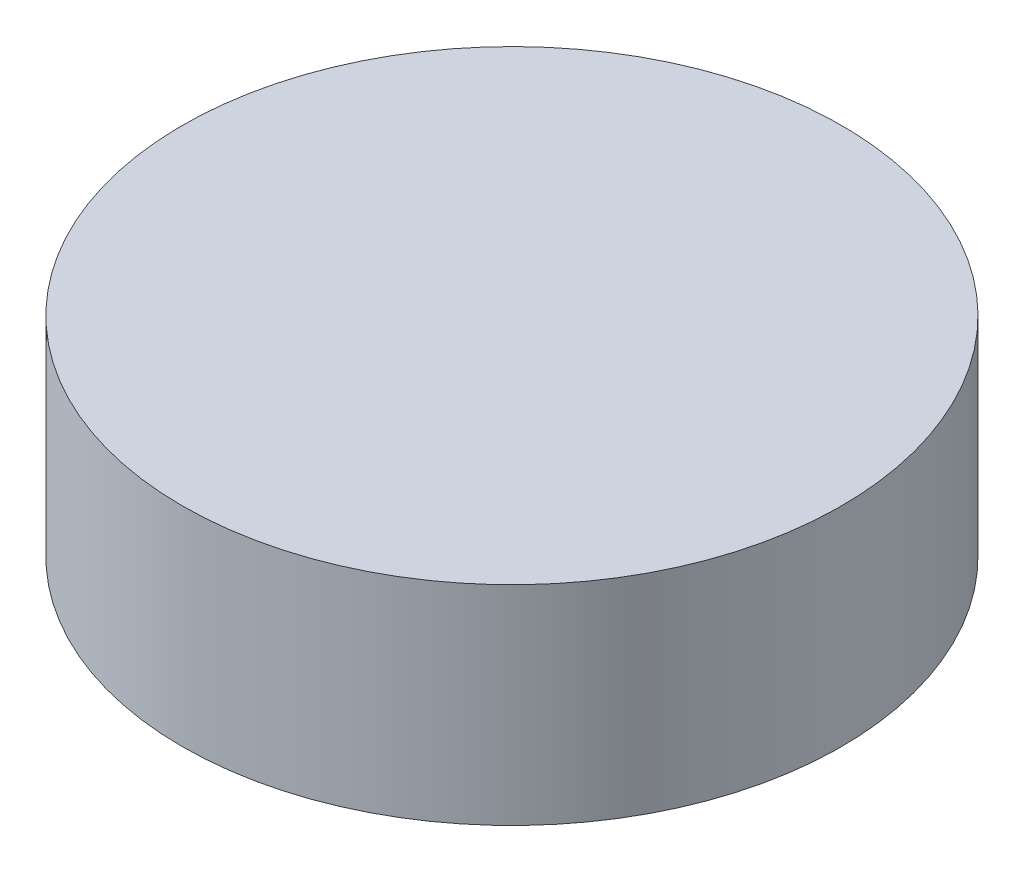
SolidWorks part; units mm, degrees
material "ABS"
ref_plane "Front Plane" through (0, 0, 0) normal (0, 0, 1) x (1, 0, 0)
ref_plane "Top Plane" through (0, 0, 0) normal (0, 1, 0) x (1, 0, 0)
ref_plane "Right Plane" through (0, 0, 0) normal (1, 0, 0) x (0, 0, -1)
ref_plane "Plane1" through (0, 93.4276, 0) normal (0, 1, 0) x (1, 0, 0)
sketch "Sketch2" plane through (0, 93.4276, 0) normal (0, 1, 0) x (1, 0, 0)
  circle A0 centre (47.2924, -96.3529) radius 63.5 construction
  circle A2 centre (47.2924, -96.3529) radius 70.25
  dimension "D1" = 6.75
extrude "Boss-Extrude1" add sketch "Sketch2" against normal up to surface (44.45 mm away)
sketch "Sketch3" plane through (0, 48.9776, 0) normal (0, -1, 0) x (1, 0, 0)
  circle A0 centre (47.2924, 96.3529) radius 63.9
  circle A1 centre (47.2924, 96.3529) radius 63.5 construction
  dimension "D1" = 0.4
extrude "Cut-Extrude1" cut sketch "Sketch3" against normal offset from surface (38.5 mm away) 0.4
